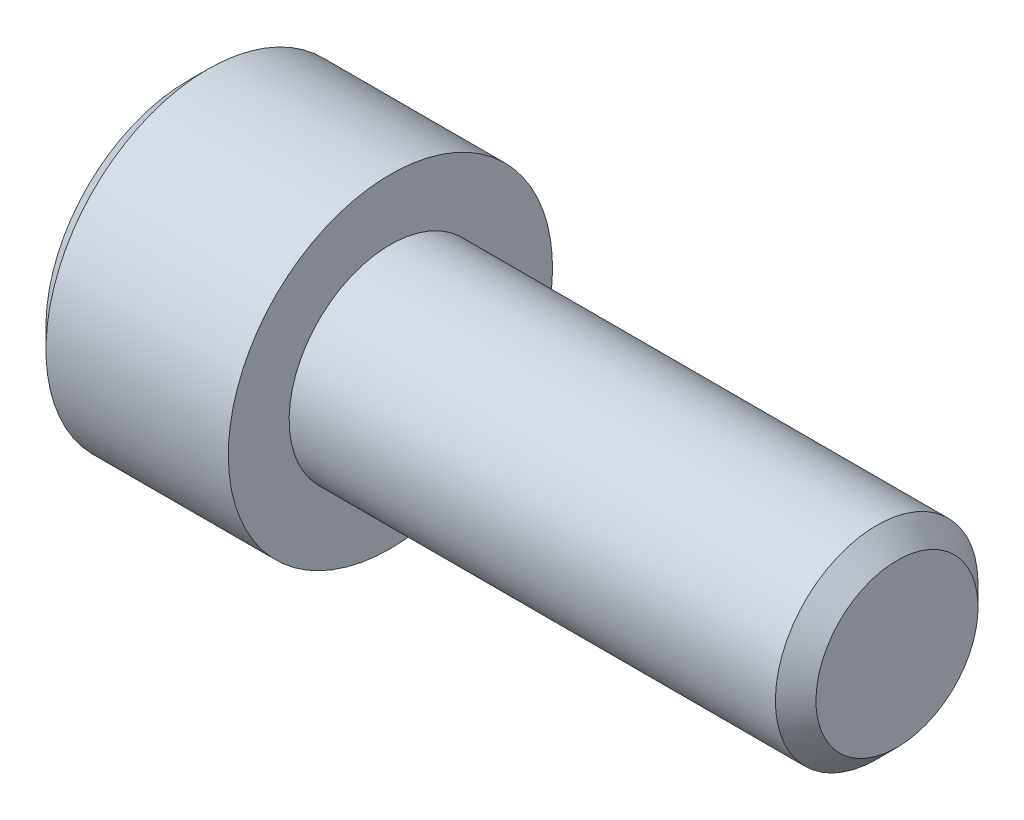
SolidWorks part; units mm, degrees
ref_plane "Front" through (0, 0, 0) normal (0, 0, 1) x (1, 0, 0)
ref_plane "Top" through (0, 0, 0) normal (0, 1, 0) x (1, 0, 0)
ref_plane "Right" through (0, 0, 0) normal (1, 0, 0) x (0, 0, -1)
sketch "Sketch1" plane through (0, 0, 0) normal (0, 0, 1) x (1, 0, 0)
  line L0 (-10, 0) -> (-10, 8)
  line L1 (-10, 0) -> (25, 0)
  line L2 (-10, 8) -> (0, 8)
  line L3 (0, 8) -> (0, 5)
  line L4 (0, 5) -> (25, 5)
  line L6 (25, 5) -> (25, 0)
  line L8 (25, 0) -> (-10, 0) construction
  dimension "D1" = 16
  dimension "D2" = 10
  dimension "D3" = 10
  dimension "D4" = 25
revolve "Revolve1" add sketch "Sketch1" angle 360 about L8
cosmetic thread "Cosmetic Thread1" parameters "D2"=8.619
sketch "Sketch2" plane through (0, 0, 0) normal (0, 0, 1) x (1, 0, 0)
  line L0 (-10, 0) -> (-10, 3.995)
  line L1 (-10, 3.995) -> (-5, 3.995)
  line L2 (-5, 3.995) -> (-3.9295, 0)
  line L3 (-10, 8) -> (-10, -8) construction
  line L4 (-3.9295, 0) -> (-10, 0) construction
  line L5 (-10, 0) -> (-3.9295, 0)
  dimension "D1" = 75
  dimension "D2" = 7.99
  dimension "D3" = 5
revolve "Cut-Revolve1" cut sketch "Sketch2" angle 360 about L4
sketch "Sketch3" plane through (-10, 0, 0) normal (1, 0, 0) x (0, 0, -1)
  line L1 (0, 4.6188) -> (-4, 2.3094)
  line L2 (-4, 2.3094) -> (-4, -2.3094)
  line L3 (-4, -2.3094) -> (0, -4.6188)
  line L4 (0, -4.6188) -> (4, -2.3094)
  line L5 (4, -2.3094) -> (4, 2.3094)
  line L6 (4, 2.3094) -> (0, 4.6188)
  circle A0 centre (0, 0) radius 4 construction
  dimension "D1" = 8
extrude "Cut-Extrude1" cut sketch "Sketch3" along normal blind 5
chamfer "Chamfer1" distance 1 angle 45 2 edges at (-10, -8, 0) (25, -5, 0)
